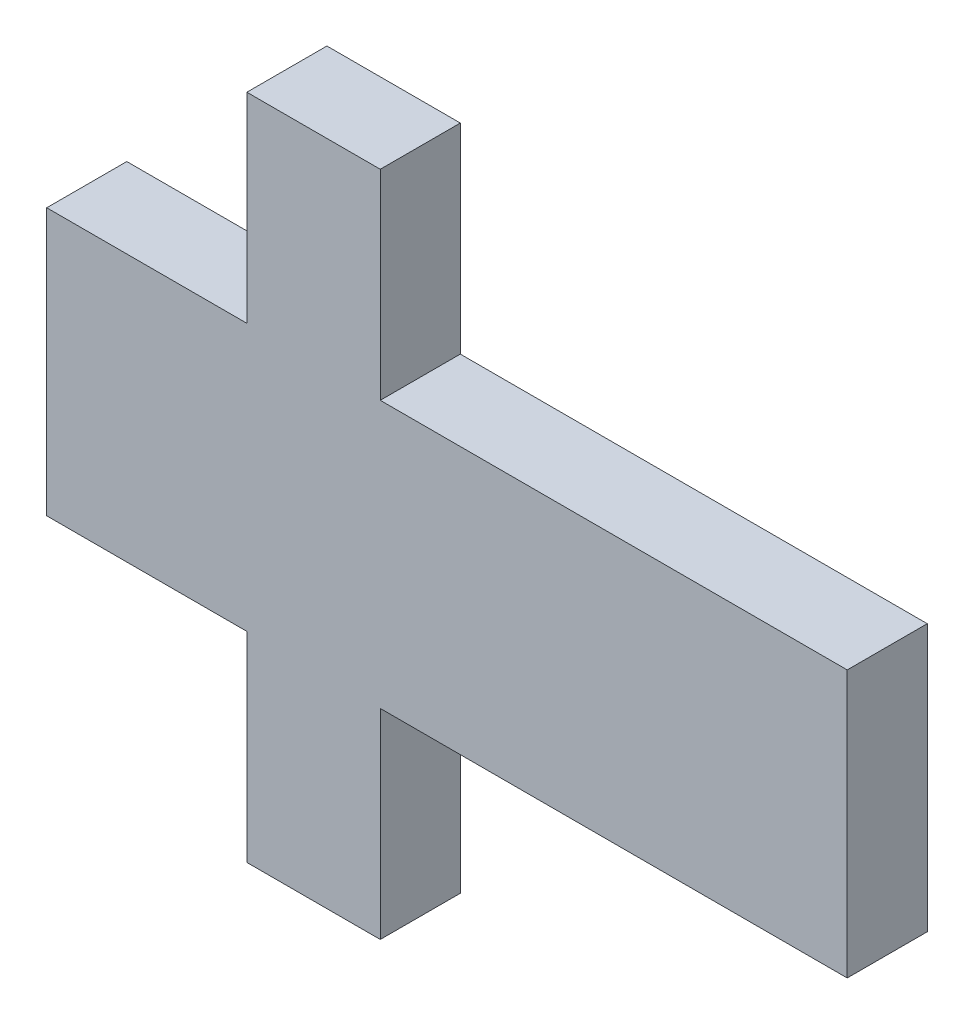
SolidWorks part; units mm, degrees
ref_plane "Front Plane" through (0, 0, 0) normal (0, 0, 1) x (1, 0, 0)
ref_plane "Top Plane" through (0, 0, 0) normal (0, 1, 0) x (1, 0, 0)
ref_plane "Right Plane" through (0, 0, 0) normal (1, 0, 0) x (0, 0, -1)
sketch "Sketch1" plane through (0, 0, 0) normal (0, 0, 1) x (1, 0, 0)
  line L1 (0, 0) -> (76.2, 0)
  line L2 (0, 0) -> (0, 25.4)
  line L3 (0, 25.4) -> (76.2, 25.4)
  line L4 (76.2, 0) -> (76.2, 25.4)
  dimension "D1" = 25.4
  dimension "D2" = 76.2
extrude "Boss-Extrude1" add sketch "Sketch1" along normal blind 7.62
sketch "Sketch2" plane through (0, 0, 0) normal (0, 0, -1) x (-1, 0, 0)
  line L0 (0, 0) -> (-76.2, 0) construction
  line L1 (-28.3886, 21.0472) -> (-32.3114, 21.0472)
  line L2 (-32.3114, 21.0472) -> (-34.2728, 17.65)
  line L3 (-34.2728, 17.65) -> (-32.3114, 14.2528)
  line L4 (-32.3114, 14.2528) -> (-28.3886, 14.2528)
  line L5 (-28.3886, 14.2528) -> (-26.4272, 17.65)
  line L6 (-26.4272, 17.65) -> (-28.3886, 21.0472)
  line L7 (-18.4886, 21.0473) -> (-22.4114, 21.0473)
  line L8 (-22.4114, 21.0473) -> (-24.3728, 17.65)
  line L9 (-24.3728, 17.65) -> (-22.4114, 14.2528)
  line L10 (-22.4114, 14.2528) -> (-18.4886, 14.2528)
  line L11 (-18.4886, 14.2528) -> (-16.5272, 17.65)
  line L12 (-16.5272, 17.65) -> (-18.4886, 21.0473)
  line L13 (-18.4886, 11.1472) -> (-22.4114, 11.1473)
  line L14 (-22.4114, 11.1473) -> (-24.3728, 7.75)
  line L15 (-24.3728, 7.75) -> (-22.4114, 4.3527)
  line L16 (-22.4114, 4.3527) -> (-18.4886, 4.3527)
  line L17 (-18.4886, 4.3527) -> (-16.5272, 7.75)
  line L18 (-16.5272, 7.75) -> (-18.4886, 11.1472)
  line L19 (-28.3886, 11.1472) -> (-32.3114, 11.1472)
  line L20 (-32.3114, 11.1472) -> (-34.2728, 7.75)
  line L21 (-34.2728, 7.75) -> (-32.3114, 4.3527)
  line L22 (-32.3114, 4.3527) -> (-28.3886, 4.3527)
  line L23 (-28.3886, 4.3527) -> (-26.4272, 7.75)
  line L24 (-26.4272, 7.75) -> (-28.3886, 11.1472)
  line L25 (0, 25.4) -> (0, 0) construction
  circle A0 centre (-30.35, 17.65) radius 3.3973 construction
  circle A1 centre (-20.45, 17.65) radius 3.3972 construction
  circle A2 centre (-20.45, 7.75) radius 3.3973 construction
  circle A3 centre (-30.35, 7.75) radius 3.3973 construction
  circle A4 centre (-25.4, 12.7) radius 0.8634
  point P39 (-20.45, 21.0472)
  dimension "D1" = 0
  dimension "D2" = 0
  dimension "D3" = 0
  dimension "D4" = 0
  dimension "D5" = 12.7
  dimension "D6" = 25.4
  dimension "D7" = 4.95
  dimension "D8" = 4.95
  dimension "D9" = 9.9
  dimension "D10" = 9.9
  dimension "D11" = 9.9
  dimension "D12" = 9.9
  dimension "D13" = 0
  dimension "D14" = 0
  dimension "D15" = 6.7945
  dimension "D16" = 6.7945
  dimension "D17" = 6.7945
  dimension "D18" = 6.7945
extrude "Cut-Extrude1" cut sketch "Sketch2" against normal blind 6.35
chamfer "Chamfer1" distance 0.508 angle 45 24 edges at (23.3921, 9.4486, 0) (23.3921, 6.0514, 0) (20.45, 4.3527, 0) (17.5079, 6.0514, 0) (17.5079, 9.4486, 0) (20.45, 11.1473, 0) (23.3921, 15.9514, 0) (20.45, 14.2528, 0) (17.5079, 15.9514, 0) (17.5079, 19.3486, 0) (20.45, 21.0473, 0) (23.3921, 19.3486, 0) (27.4079, 9.4486, 0) (27.4079, 6.0514, 0) (30.35, 4.3527, 0) (33.2921, 6.0514, 0) (33.2921, 9.4486, 0) (30.35, 11.1472, 0) (27.4079, 15.9514, 0) (30.35, 14.2528, 0) (27.4079, 19.3486, 0) (30.35, 21.0472, 0) (33.2921, 19.3486, 0) (33.2921, 15.9514, 0)
sketch "Sketch3" plane through (0, 0, 0) normal (0, 0, -1) x (-1, 0, 0)
  line L0 (0, 0) -> (-76.2, 0) construction
  line L5 (-19.05, 0) -> (-31.75, 0)
  line L6 (-19.05, 0) -> (-19.05, -19.05)
  line L7 (-19.05, -19.05) -> (-31.75, -19.05)
  line L8 (-31.75, 0) -> (-31.75, -19.05)
  line L9 (-76.2, 25.4) -> (0, 25.4) construction
  line L10 (-19.05, 25.4) -> (-31.75, 25.4)
  line L11 (-19.05, 25.4) -> (-19.05, 44.45)
  line L12 (-19.05, 44.45) -> (-31.75, 44.45)
  line L13 (-31.75, 25.4) -> (-31.75, 44.45)
  circle A0 centre (-25.4, 12.7) radius 0.8634 construction
  dimension "D1" = 0
  dimension "D2" = 0
  dimension "D3" = 12.7
  dimension "D4" = 6.35
  dimension "D5" = 19.05
  dimension "D6" = 19.05
extrude "Boss-Extrude2" add sketch "Sketch3" against normal blind 7.62
equation "\"standoff\"= 0.2675"
equation "\"D15@Sketch2\"=\"standoff\""
equation "\"D16@Sketch2\"=\"standoff\""
equation "\"D17@Sketch2\"=\"standoff\""
equation "\"D18@Sketch2\"=\"standoff\""
